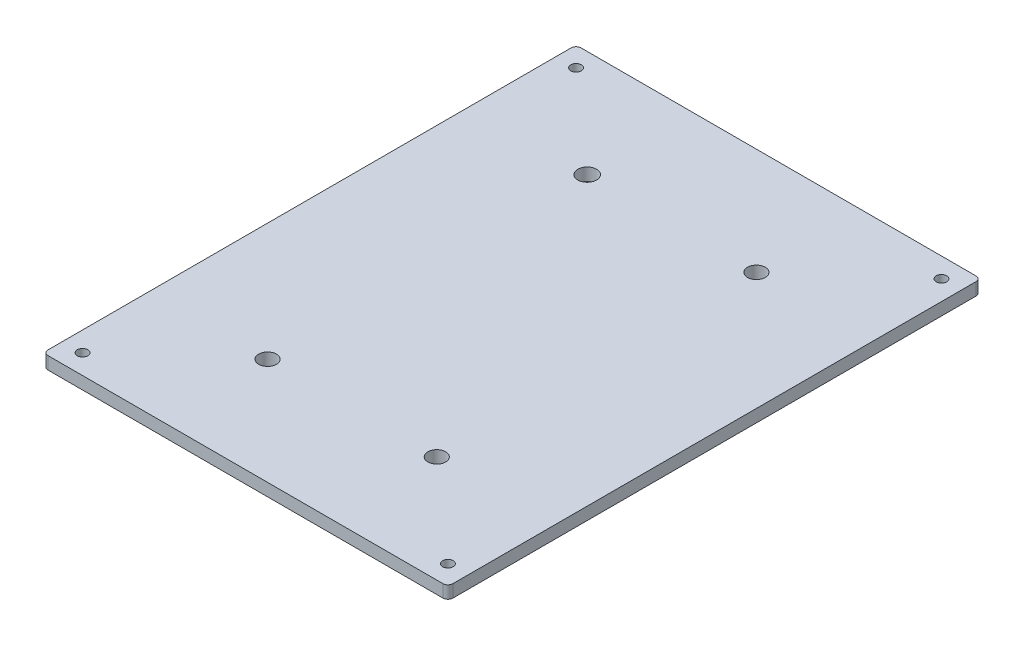
SolidWorks part; units mm, degrees
ref_plane "Front Plane" through (0, 0, 0) normal (0, 0, 1) x (1, 0, 0)
ref_plane "Top Plane" through (0, 0, 0) normal (0, 1, 0) x (1, 0, 0)
ref_plane "Right Plane" through (0, 0, 0) normal (1, 0, 0) x (0, 0, -1)
sketch "Sketch1" plane through (0, 0, 0) normal (0, 1, 0) x (1, 0, 0)
  line L1 (102.55, 135) -> (-102.55, 135)
  line L2 (102.55, 135) -> (102.55, -135)
  line L3 (102.55, -135) -> (-102.55, -135)
  line L4 (-102.55, 135) -> (-102.55, -135)
  line L5 (102.55, 135) -> (-102.55, -135) construction
  line L6 (102.55, -135) -> (-102.55, 135) construction
  point P0 (0, 0)
  dimension "D1" = 270
  dimension "D2" = 205.1
extrude "Boss-Extrude1" add sketch "Sketch1" along normal blind 6.35
sketch "Sketch2" plane through (0, 6.35, 0) normal (0, 1, 0) x (1, 0, 0)
  line L0 (102.55, 135) -> (-102.55, 135) construction
  line L1 (-42.8625, 80.9625) -> (42.8625, 80.9625) construction
  line L2 (-42.8625, 80.9625) -> (-42.8625, -80.9625) construction
  line L3 (-42.8625, -80.9625) -> (42.8625, -80.9625) construction
  line L4 (42.8625, 80.9625) -> (42.8625, -80.9625) construction
  line L5 (-42.8625, 80.9625) -> (42.8625, -80.9625) construction
  line L6 (-42.8625, -80.9625) -> (42.8625, 80.9625) construction
  line L7 (0, 135) -> (0, 80.9625) construction
  line L8 (0, 80.9625) -> (0, -80.9625) construction
  line L9 (0, -80.9625) -> (0, -135) construction
  line L10 (-102.55, -135) -> (102.55, -135) construction
  line L11 (42.8625, 0) -> (102.55, 0) construction
  line L12 (102.55, -135) -> (102.55, 135) construction
  line L13 (-42.8625, 0) -> (-102.55, 0) construction
  line L14 (-102.55, 135) -> (-102.55, -135) construction
  circle A0 centre (-42.8625, 80.9625) radius 4.7625
  circle A1 centre (-42.8625, -80.9625) radius 4.5
  circle A2 centre (42.8625, -80.9625) radius 4.5
  circle A4 centre (42.8625, 80.9625) radius 4.5
  point P5 (0, 0)
  dimension "D4" = 9.525
  dimension "D2" = 85.725
  dimension "D3" = 161.925
sketch "Sketch3" plane through (0, 6.35, 0) normal (0, 1, 0) x (-1, 0, 0)
  line L0 (92.55, -135) -> (92.55, 135) construction
  line L1 (-102.55, -135) -> (102.55, -135) construction
  line L2 (102.55, 135) -> (-102.55, 135) construction
  line L3 (102.55, 125) -> (-102.55, 125) construction
  line L4 (102.55, -135) -> (102.55, 135) construction
  line L5 (-102.55, 135) -> (-102.55, -135) construction
  line L6 (-92.55, -135) -> (-92.55, 135) construction
  circle A0 centre (92.55, 125) radius 2.665
  circle A1 centre (-92.55, 125) radius 2.665
  circle A2 centre (-92.55, -125) radius 2.665
  circle A3 centre (92.55, -125) radius 2.665
  dimension "D4" = 10
  dimension "D5" = 10
  dimension "D6" = 5.33
  dimension "D1" = 10
  dimension "D2" = 10
  dimension "D3" = 10
extrude "Cut-Extrude2" cut sketch "Sketch3" against normal up to next
extrude "Cut-Extrude3" cut sketch "Sketch2" against normal up to next
fillet "Fillet1" radius 2.54 4 edges at (-102.55, 3.175, -135) (102.55, 3.175, -135) (102.55, 3.175, 135) (-102.55, 3.175, 135)
